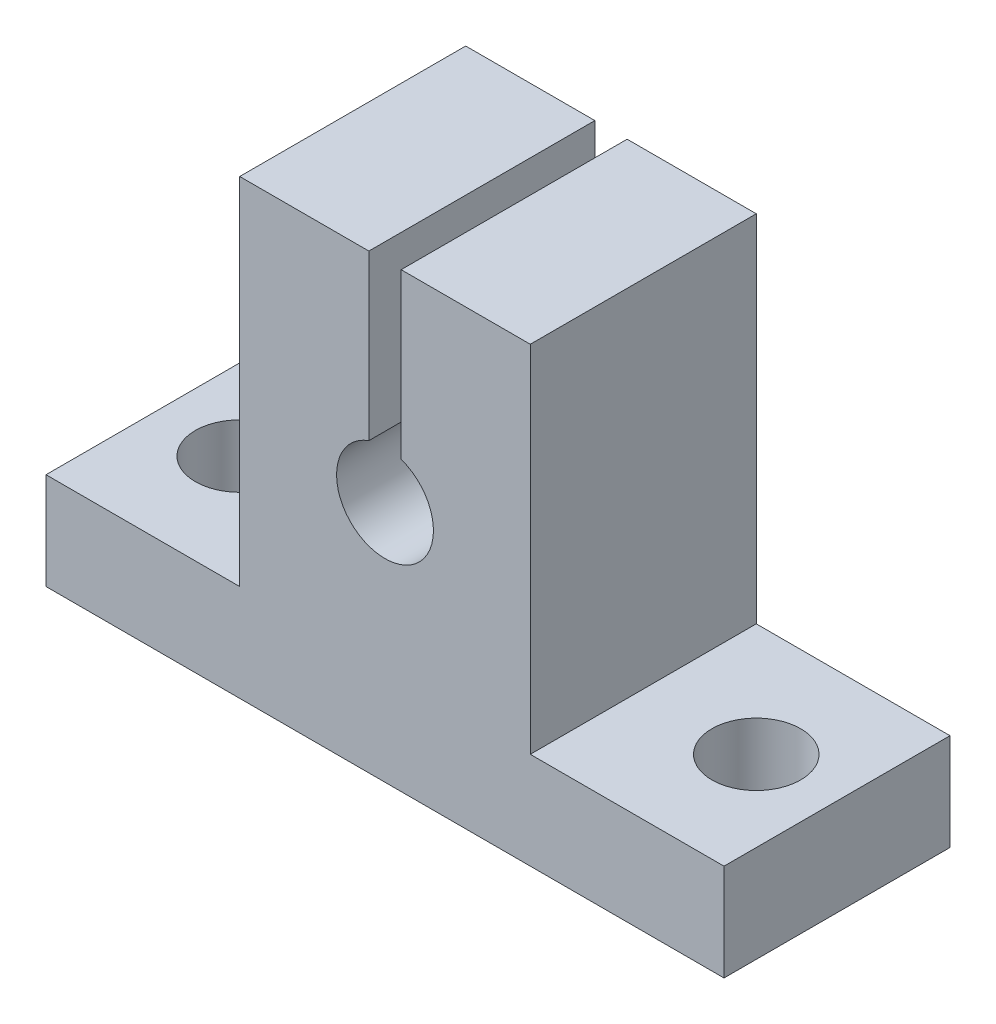
SolidWorks part; units mm, degrees
ref_plane "前视基准面" through (0, 0, 0) normal (0, 0, 1) x (1, 0, 0)
ref_plane "上视基准面" through (0, 0, 0) normal (0, 1, 0) x (1, 0, 0)
ref_plane "右视基准面" through (0, 0, 0) normal (1, 0, 0) x (0, 0, -1)
other "Configuration Table"
sketch "草图1" plane through (0, 0, 0) normal (0, 0, 1) x (1, 0, 0)
  line L0 (0, 0) -> (0, 16251.5163) construction
  line L1 (-1, 0) -> (-9, 0)
  line L2 (-9, 0) -> (-9, -22)
  line L3 (-9, -22) -> (-21, -22)
  line L4 (-21, -22) -> (-21, -28)
  line L5 (-21, -28) -> (21, -28)
  line L6 (21, -22) -> (21, -28)
  line L7 (9, -22) -> (21, -22)
  line L8 (9, 0) -> (9, -22)
  line L9 (1, 0) -> (9, 0)
  line L10 (-1, 0) -> (-1, -10.1716)
  line L11 (1, 0) -> (1, -10.1716)
  arc A0 (-1, -10.1716) -> (1, -10.1716) centre (0, -13) ccw
  point P10 (0, -28)
  dimension "D5" = 6
  dimension "D1" = 21
  dimension "D2" = 18
  dimension "D3" = 28
  dimension "D4" = 6
  dimension "D6" = 15
  dimension "D7" = 2
extrude "凸台-拉伸1" add sketch "草图1" along normal blind 14
sketch "草图2" plane through (0, -22, 0) normal (0, 1, 0) x (1, 0, 0)
  line L0 (0, 0) -> (0, -14) construction
  line L1 (-3, -14) -> (3, -14) construction
  line L2 (-21, -14) -> (-21, 0) construction
  circle A0 centre (-16, -7) radius 2.75
  circle A1 centre (16, -7) radius 2.75
  point P9 (-21, -7)
  dimension "D1" = 5.5
  dimension "D2" = 32
extrude "切除-拉伸1" cut sketch "草图2" against normal through all
